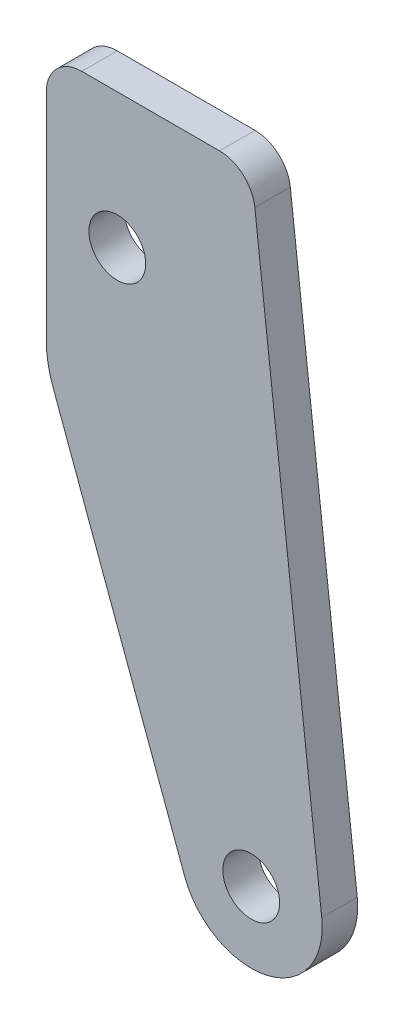
SolidWorks part; units mm, degrees
ref_plane "Płaszczyzna przednia" through (0, 0, 0) normal (0, 0, 1) x (1, 0, 0)
ref_plane "Płaszczyzna górna" through (0, 0, 0) normal (0, 1, 0) x (1, 0, 0)
ref_plane "Płaszczyzna prawa" through (0, 0, 0) normal (1, 0, 0) x (0, 0, -1)
sketch "Szkic1" plane through (0, 0, 0) normal (0, 0, 1) x (1, 0, 0)
  line L3 (-55.8908, 93.9848) -> (-18.7698, -6.906)
  line L4 (-47.7361, 175) -> (-17.7361, 175)
  line L5 (-57.7361, 165) -> (-57.7361, 104.3439)
  line L6 (-57.7361, 99) -> (-17.7361, 99)
  line L7 (-17.7361, 175) -> (-17.7361, 99)
  line L8 (-57.7361, 175) -> (-17.7361, 99) construction
  line L9 (-57.7361, 99) -> (-17.7361, 175) construction
  line L10 (-17.7361, 175) -> (-8.9156, 175)
  line L11 (1.0189, 166.1429) -> (19.869, 2.2857)
  circle A0 centre (0, 0) radius 8
  circle A1 centre (0, 0) radius 20
  arc A4 (1.0189, 166.1429) -> (-8.9156, 175) centre (-8.9156, 165) ccw
  arc A5 (-47.7361, 175) -> (-57.7361, 165) centre (-47.7361, 165) ccw
  arc A6 (-57.7361, 104.3439) -> (-55.8908, 93.9848) centre (-27.7361, 104.3439) ccw
  circle A7 centre (-37.7361, 137) radius 8
  point P18 (0, 175)
  dimension "D3" = 76
  dimension "D5" = 57.7361
  dimension "D8" = 40
  dimension "D9" = 16
  dimension "D13" = 10
  dimension "D14" = 10
  dimension "D15" = 30
  dimension "D6" = 16
  dimension "D2" = 99
  dimension "D4" = 40
  dimension "D12" = 17.7361
extrude "Dodanie-wyciągnięcie3" add sketch "Szkic1" along normal blind 10
